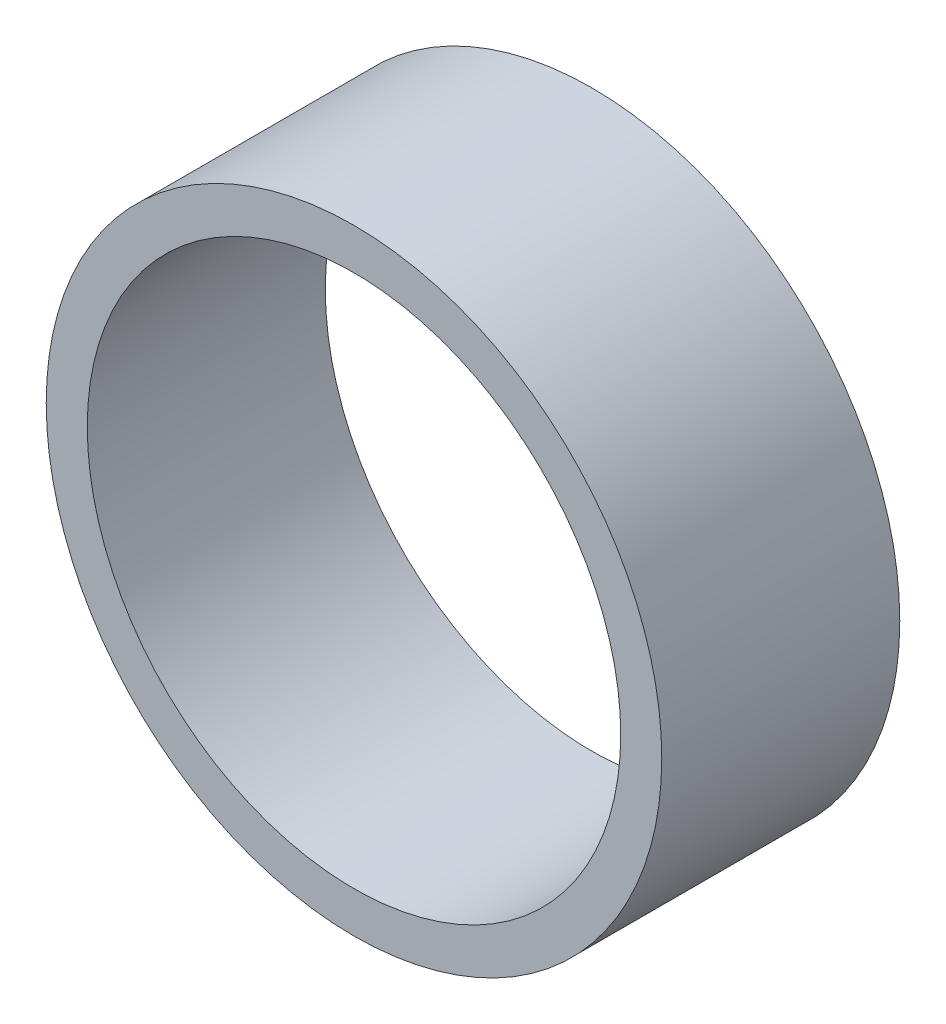
SolidWorks part; units mm, degrees
ref_plane "Front Plane" through (0, 0, 0) normal (0, 0, 1) x (1, 0, 0)
ref_plane "Top Plane" through (0, 0, 0) normal (0, 1, 0) x (1, 0, 0)
ref_plane "Right Plane" through (0, 0, 0) normal (1, 0, 0) x (0, 0, -1)
sketch "Sketch1" plane through (0, 0, 0) normal (0, 0, 1) x (1, 0, 0)
  circle A0 centre (-43.2127, 1.4419) radius 7.5
  dimension "D1" = 15
extrude "Boss-Extrude1" add sketch "Sketch1" along normal blind 5.8
sketch "Sketch2" plane through (0, 0, 5.8) normal (0, 0, 1) x (1, 0, 0)
  circle A0 centre (-43.2127, 1.4419) radius 6.5
  dimension "D1" = 13
extrude "Cut-Extrude1" cut sketch "Sketch2" against normal blind 5.8
